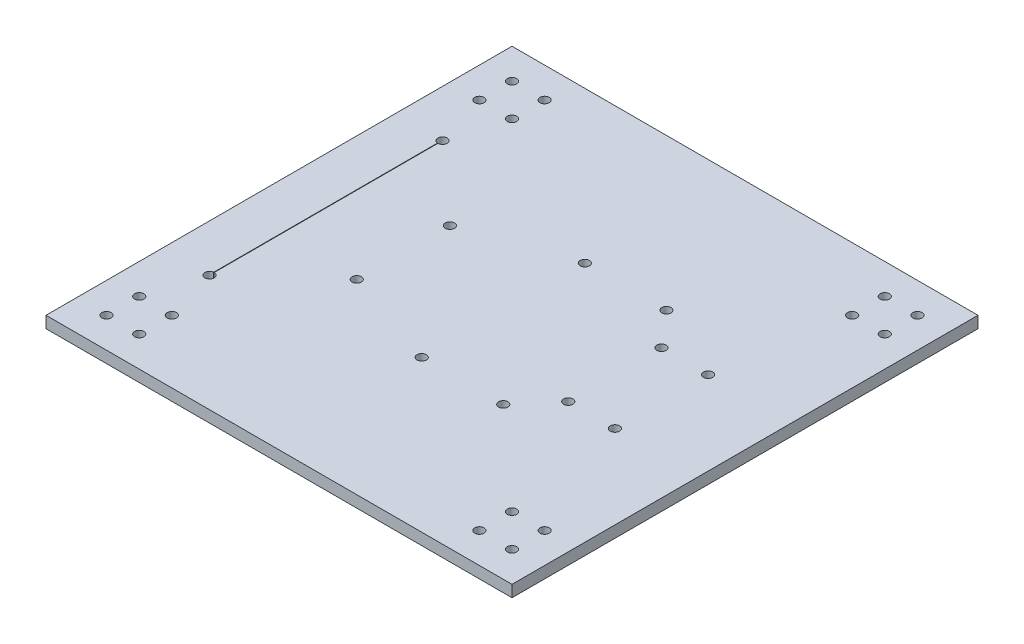
SolidWorks part; units mm, degrees
ref_plane "前视基准面" through (0, 0, 0) normal (0, 0, 1) x (1, 0, 0)
ref_plane "上视基准面" through (0, 0, 0) normal (0, 1, 0) x (1, 0, 0)
ref_plane "右视基准面" through (0, 0, 0) normal (1, 0, 0) x (0, 0, -1)
sketch "草图1" plane through (0, 0, 0) normal (0, 1, 0) x (1, 0, 0)
  line L0 (-100, 0) -> (100, 0)
  line L1 (-100, 100) -> (100, 100)
  line L2 (-100, 100) -> (-100, -100)
  line L3 (-100, -100) -> (100, -100)
  line L4 (100, 100) -> (100, -100)
  line L5 (-100, 100) -> (100, -100) construction
  line L6 (-100, -100) -> (100, 100) construction
  line L7 (-79.8058, 50) -> (-79.8058, 0)
  line L8 (-79.8058, 0) -> (-79.8058, -50)
  line L9 (-46.6325, 0) -> (-46.6325, 20)
  line L10 (-46.6325, 20) -> (-46.6325, 0)
  line L11 (-46.6325, -20) -> (-46.6325, 0)
  line L12 (13.752, 0) -> (54.165, 0)
  line L13 (-80, 80) -> (80, 80)
  line L14 (-3.748, 35) -> (31.252, 35)
  line L15 (-3.748, 35) -> (-3.748, -35)
  line L16 (-3.748, -35) -> (31.252, -35)
  line L17 (31.252, 35) -> (31.252, -35)
  line L18 (-3.748, 35) -> (31.252, -35) construction
  line L19 (-3.748, -35) -> (31.252, 35) construction
  line L20 (44.165, 20) -> (64.165, 20)
  line L21 (44.165, 20) -> (44.165, -20)
  line L22 (44.165, -20) -> (64.165, -20)
  line L23 (64.165, 20) -> (64.165, -20)
  line L24 (44.165, 20) -> (64.165, -20) construction
  line L25 (44.165, -20) -> (64.165, 20) construction
  line L26 (80, 80) -> (80, -80)
  line L27 (80, -80) -> (-80, -80)
  line L28 (-80, -80) -> (-80, 80)
  line L29 (-73, -80) -> (-73, -73)
  line L30 (-87, 87) -> (-73, 87)
  line L31 (-87, 87) -> (-87, 73)
  line L32 (-87, 73) -> (-73, 73)
  line L33 (-73, 87) -> (-73, 73)
  line L34 (-87, 87) -> (-73, 73) construction
  line L35 (-87, 73) -> (-73, 87) construction
  line L36 (73, 87) -> (87, 87)
  line L37 (73, 87) -> (73, 73)
  line L38 (73, 73) -> (87, 73)
  line L39 (87, 87) -> (87, 73)
  line L40 (73, 87) -> (87, 73) construction
  line L41 (73, 73) -> (87, 87) construction
  line L42 (73, -73) -> (87, -73)
  line L43 (73, -73) -> (73, -87)
  line L44 (73, -87) -> (87, -87)
  line L45 (87, -73) -> (87, -87)
  line L46 (73, -73) -> (87, -87) construction
  line L47 (73, -87) -> (87, -73) construction
  line L48 (-87, -73) -> (-73, -73)
  line L49 (-87, -73) -> (-87, -87)
  line L50 (-87, -87) -> (-73, -87)
  line L51 (-73, -73) -> (-73, -87)
  line L52 (-87, -73) -> (-73, -87) construction
  line L53 (-87, -87) -> (-73, -73) construction
  line L54 (-80, 73) -> (-73, 73)
  line L55 (73, 80) -> (73, 73)
  line L56 (73, -80) -> (73, -73)
  circle A0 centre (-79.8058, 50) radius 2
  circle A1 centre (-79.8058, -50) radius 2
  circle A2 centre (-46.6325, 20) radius 2
  circle A3 centre (-46.6325, -20) radius 2
  circle A4 centre (-3.748, 35) radius 2
  circle A5 centre (31.252, 35) radius 2
  circle A6 centre (-3.748, -35) radius 2
  circle A7 centre (31.252, -35) radius 2
  circle A8 centre (44.165, -20) radius 2
  circle A9 centre (64.165, -20) radius 2
  circle A10 centre (44.165, 20) radius 2
  circle A11 centre (64.165, 20) radius 2
  circle A12 centre (-87, 87) radius 2
  circle A13 centre (-87, 73) radius 2
  circle A14 centre (-73, 73) radius 2
  circle A15 centre (-73, 87) radius 2
  circle A17 centre (73, 73) radius 2
  circle A18 centre (87, 73) radius 2
  circle A20 centre (-73, -73) radius 2
  circle A21 centre (-87, -73) radius 2
  circle A24 centre (73, -73) radius 2
  circle A25 centre (73, -87) radius 2
  circle A26 centre (87, -73) radius 2
  circle A28 centre (73, 87) radius 2
  circle A29 centre (87, 87) radius 2
  circle A30 centre (-87, -87) radius 2
  circle A31 centre (-73, -87) radius 2
  circle A32 centre (87, -87) radius 2
  point P0 (0, 0)
  dimension "D5" = 20
  dimension "D7" = 35
  dimension "D11" = 14
  dimension "D19" = 160
  dimension "D1" = 200
  dimension "D2" = 200
  dimension "D3" = 50
  dimension "D4" = 50
  dimension "D6" = 20
  dimension "D8" = 70
  dimension "D9" = 20
  dimension "D10" = 40
  dimension "D12" = 14
  dimension "D13" = 14
  dimension "D14" = 14
  dimension "D15" = 14
  dimension "D16" = 14
  dimension "D17" = 14
  dimension "D18" = 14
extrude "凸台-拉伸2" add sketch "草图1" along normal blind 5
